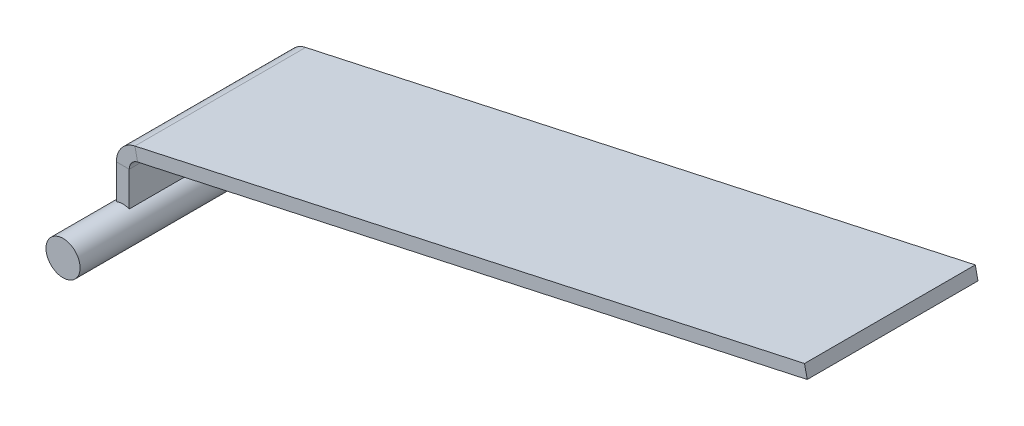
SolidWorks part; units mm, degrees
ref_plane "Front Plane" through (0, 0, 0) normal (0, 0, 1) x (1, 0, 0)
ref_plane "Top Plane" through (0, 0, 0) normal (0, 1, 0) x (1, 0, 0)
ref_plane "Right Plane" through (0, 0, 0) normal (1, 0, 0) x (0, 0, -1)
sketch "Sketch1" plane through (0, 0, 0) normal (0, 0, 1) x (1, 0, 0)
  line L0 (0, 0) -> (0, 1.178)
  line L1 (0.3145, 1.5688) -> (16, 5)
  arc A0 (0, 1.178) -> (0.3145, 1.5688) centre (0.4, 1.178) cw
  point P5 (0, 1.5)
  point P6 (0, 1.5)
  dimension "D3" = 5
  dimension "D1" = 16
  dimension "D4" = 0.4
  dimension "D2" = 1.5
sketch "Sketch2" plane through (0, 0, 0) normal (0, 1, 0) x (1, 0, 0)
  line L1 (-0.15, 2) -> (0.15, 2)
  line L2 (-0.15, 2) -> (-0.15, -2)
  line L3 (-0.15, -2) -> (0.15, -2)
  line L4 (0.15, 2) -> (0.15, -2)
  line L5 (-0.15, 2) -> (0.15, -2) construction
  line L6 (-0.15, -2) -> (0.15, 2) construction
  point P0 (0, 0)
  dimension "D1" = 4
  dimension "D2" = 0.3
sweep "Sweep1" add profiles "Sketch2" path "Sketch1"
sketch "Sketch4" plane through (0, 0, 0) normal (0, 0, 1) x (1, 0, 0)
  line L0 (-0.15, 0) -> (0.15, 0) construction
  circle A0 centre (0, 0) radius 0.4
  dimension "D1" = 0.8
extrude "Boss-Extrude1" add sketch "Sketch4" along normal mid plane 6.8
